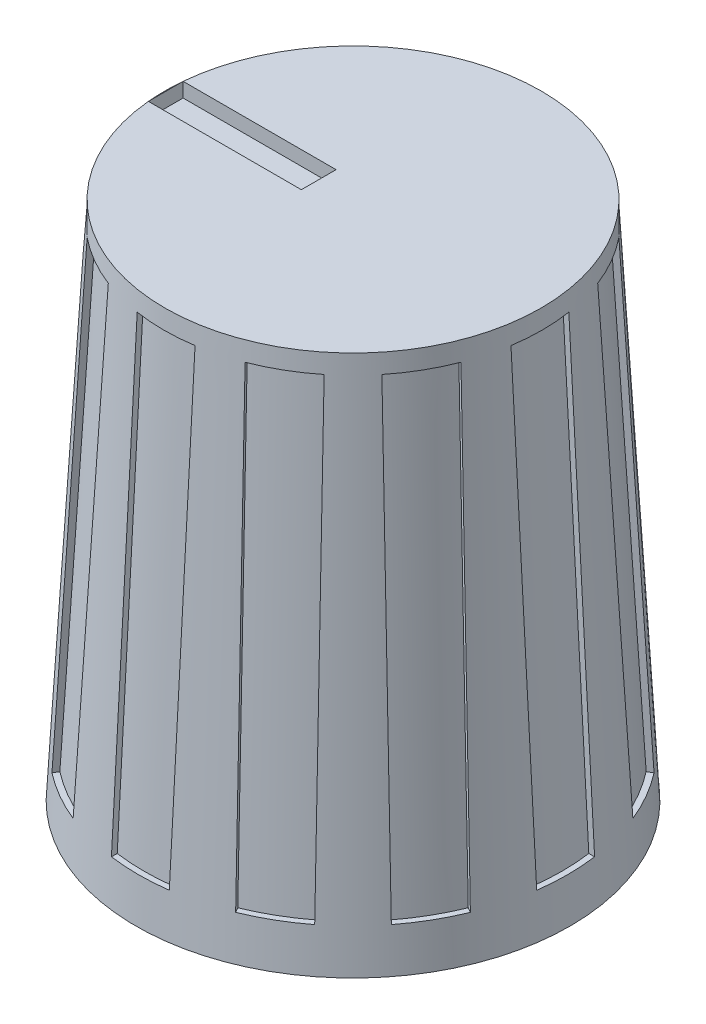
SolidWorks part; units mm, degrees
ref_plane "Plan de face" through (0, 0, 0) normal (0, 0, 1) x (1, 0, 0)
ref_plane "Plan de dessus" through (0, 0, 0) normal (0, 1, 0) x (1, 0, 0)
ref_plane "Plan de droite" through (0, 0, 0) normal (1, 0, 0) x (0, 0, -1)
sketch "Esquisse1" plane through (0, 0, 0) normal (0, 0, 1) x (1, 0, 0)
  line L0 (0, 0) -> (-7.5, 0)
  line L1 (-7.5, 0) -> (-6.5, 18)
  line L2 (-6.5, 18) -> (0, 18)
  line L3 (0, 18) -> (0, 0)
  dimension "D1" = 6.5
  dimension "D2" = 7.5
  dimension "D3" = 18
revolve "Révolution1" add sketch "Esquisse1" angle 360 about L3
sketch "Esquisse2" plane through (0, 0, 0) normal (0, 0, 1) x (1, 0, 0)
  line L0 (0, 0) -> (0, 18) construction
  line L1 (6.5, 18) -> (-6.5, 18) construction
ref_plane "Plan1" through (0, 0, 10) normal (0, 0, 1) x (1, 0, 0)
sketch "Esquisse3" plane through (0, 0, 10) normal (0, 0, 1) x (1, 0, 0)
  line L0 (-1, 17.3567) -> (1, 17.3567)
  line L1 (-1, 17.3567) -> (-1, 1.5)
  line L2 (1, 17.3567) -> (1, 1.5)
  line L3 (-1, 1.5) -> (1, 1.5)
  line L4 (-7.5, 0) -> (7.5, 0) construction
  dimension "D1" = 2
  dimension "D2" = 1.5
extrude "Enlèv. mat.-Extru.1" cut sketch "Esquisse3" against normal blind 0.2 from surface starting at face at (-7.5, 0, 0)
sketch "Esquisse4" plane through (0, 0, 0) normal (0, -1, 0) x (1, 0, 0)
  circle A0 centre (0, 0) radius 2.95
  dimension "D1" = 5.9
extrude "Enlèv. mat.-Extru.2" cut sketch "Esquisse4" against normal blind 6 draft 3
pattern_circular "Répétition circulaire4" count 12 over 360 about axis through (0, 0, 0) along (0, 1, 0) of "Enlèv. mat.-Extru.1"
ref_plane "Plan2" through (0, 20, 0) normal (0, 1, 0) x (1, 0, 0)
sketch "Esquisse5" plane through (0, 20, 0) normal (0, 1, 0) x (1, 0, 0)
  line L0 (-6.4722, 0.6) -> (-1.1851, 0.6)
  line L1 (-6.4722, 0.6) -> (-6.4722, -0.6)
  line L2 (-1.1851, 0.6) -> (-1.1851, -0.6)
  line L3 (-6.4722, -0.6) -> (-1.1851, -0.6)
  line L4 (-6.2588, -1) -> (-7.1489, -1) construction
  circle A0 centre (0, 0) radius 6.5 construction
  point P4 (-1.1851, 0)
  dimension "D1" = 0.4
extrude "Enlèv. mat.-Extru.3" cut sketch "Esquisse5" against normal blind 2.5
